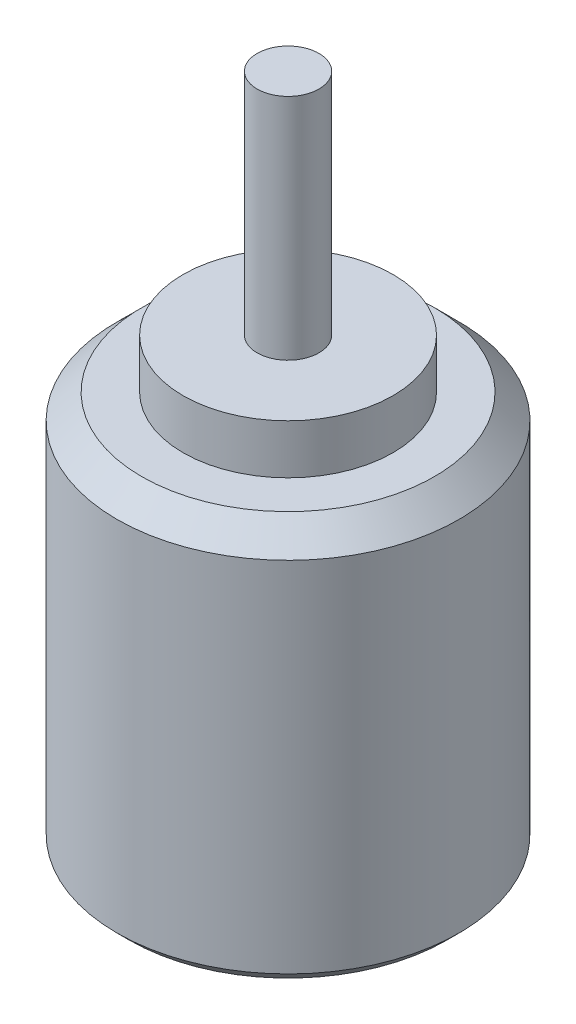
SolidWorks part; units mm, degrees
ref_plane "前视基准面" through (0, 0, 0) normal (0, 0, 1) x (1, 0, 0)
ref_plane "上视基准面" through (0, 0, 0) normal (0, 1, 0) x (1, 0, 0)
ref_plane "右视基准面" through (0, 0, 0) normal (1, 0, 0) x (0, 0, -1)
sketch "草图1" plane through (0, 0, 0) normal (0, 1, 0) x (1, 0, 0)
  circle A0 centre (0, 0) radius 13.85
  dimension "D1" = 27.7
extrude "凸台-拉伸1" add sketch "草图1" along normal blind 32
sketch "草图2" plane through (0, 0, 0) normal (0, -1, 0) x (1, 0, 0)
  circle A0 centre (0, 0) radius 2.5
  dimension "D1" = 5
extrude "凸台-拉伸2" add sketch "草图2" along normal blind 2.5
sketch "草图3" plane through (0, 32, 0) normal (0, 1, 0) x (1, 0, 0)
  circle A0 centre (0, 0) radius 8.5
  dimension "D1" = 17
extrude "凸台-拉伸3" add sketch "草图3" along normal blind 4
sketch "草图4" plane through (0, 36, 0) normal (0, 1, 0) x (1, 0, 0)
  circle A0 centre (0, 0) radius 2.5
  dimension "D1" = 5
extrude "凸台-拉伸4" add sketch "草图4" along normal blind 18.5
chamfer "倒角1" distance 2 angle 45 1 edges at (0, 32, 13.85)
chamfer "倒角2" distance 1 angle 45 1 edges at (0, 0, 13.85)
sketch "草图5" plane through (0, 0, 0) normal (0, -1, 0) x (1, 0, 0)
  line L0 (-9.3, 0) -> (9.3, 0) construction
  line L1 (0, 7.8) -> (0, -7.8) construction
  circle A0 centre (0, 7.8) radius 1.35
  circle A1 centre (-9.3, 0) radius 1.35
  circle A2 centre (0, -7.8) radius 1.35
  circle A3 centre (9.3, 0) radius 1.35
  point P5 (0, 0)
  point P9 (0, 0)
  dimension "D3" = 2.7
  dimension "D1" = 15.6
  dimension "D2" = 18.6
extrude "切除-拉伸1" cut sketch "草图5" against normal blind 3
